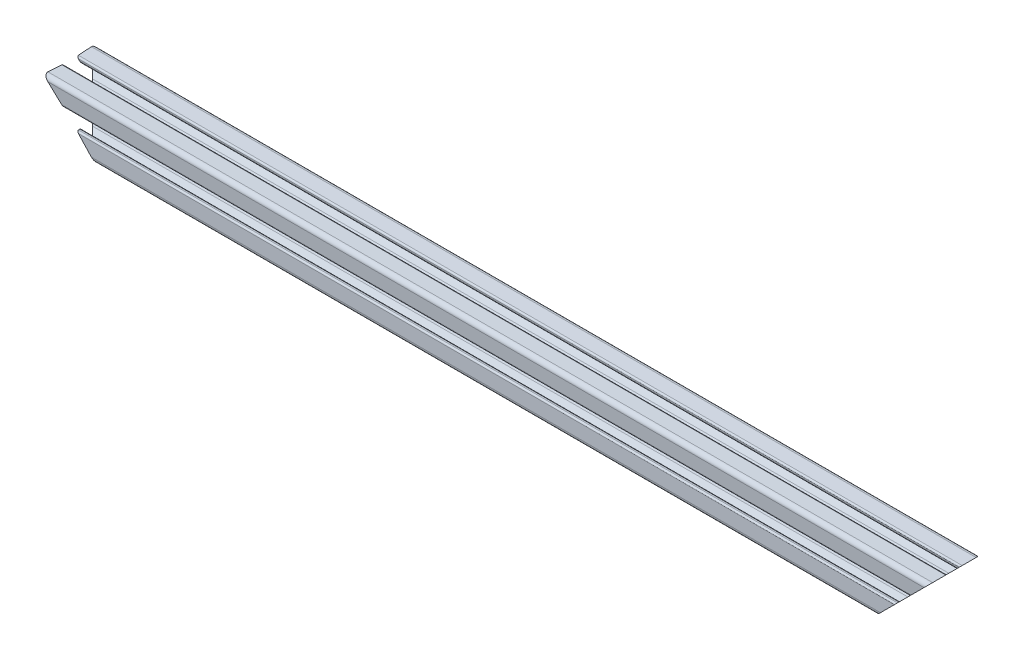
SolidWorks part; units mm, degrees
ref_plane "Front Plane" through (0, 0, 0) normal (0, 0, 1) x (1, 0, 0)
ref_plane "Top Plane" through (0, 0, 0) normal (0, 1, 0) x (1, 0, 0)
ref_plane "Right Plane" through (0, 0, 0) normal (1, 0, 0) x (0, 0, -1)
sketch "Sketch1" plane through (0, 0, 0) normal (1, 0, 0) x (0, 0, -1)
  line L0 (0, -12.7) -> (0, 12.7) construction
  line L1 (-7.874, 12.7) -> (7.874, 12.7) construction
  line L2 (-12.7, 0) -> (12.7, 0) construction
  line L3 (-7.874, 12.7) -> (-7.874, 4.826) construction
  line L4 (-3.302, 12.7) -> (3.302, 12.7) construction
  line L5 (-12.7, -12.7) -> (12.7, -12.7) construction
  line L6 (-12.7, 12.7) -> (12.7, 12.7) construction
  circle A0 centre (0, 0) radius 2.54 construction
  point P7 (0, 12.7)
  point P10 (0, 0)
  point P13 (0, 0)
  point P16 (0, 12.7)
  point P17 (-3.302, 12.7)
  point P18 (3.302, 12.7)
  point P21 (0, -12.7)
  point P24 (0, 12.7)
  dimension "Center Hole Diameter" = 5.08
  dimension "Rail Width" = 25.4
  dimension "Rail Height" = 25.4
  dimension "T-Slot Depth" = 7.874
  dimension "D1" = 15.748
  dimension "T-Slot Width" = 6.604
  dimension "D2" = 12.7
sketch "Sketch2" plane through (0, 0, 0) normal (0, 0, 1) x (1, 0, 0)
  line L0 (-215.5261, 0) -> (215.5261, 0) construction
  line L1 (0, 0) -> (0, 26.104) construction
  line L2 (215.5261, -12.7) -> (215.5261, 12.7) construction
  line L3 (-215.5261, -12.7) -> (-215.5261, 12.7) construction
  point P3 (-177.4261, 0)
  point P8 (0, 0)
  point P9 (177.4261, 0)
  point P12 (215.5261, 0)
  point P15 (-215.5261, 0)
  dimension "Length" = 431.0523
  dimension "D1" = 38.1
  dimension "D2" = 25.4
sketch "Sketch3" plane through (0, 0, 0) normal (1, 0, 0) x (0, 0, -1)
  line L0 (0, 4.826) -> (1.9842, 4.826)
  line L1 (0, -12.7) -> (0, 12.7) construction
  line L2 (4.2293, 5.7559) -> (7.5866, 9.1132)
  line L6 (7.0212, 10.4136) -> (4.0906, 10.3112)
  line L7 (3.302, 11.0728) -> (3.302, 11.7082)
  line L8 (-7.874, 12.7) -> (7.874, 12.7) construction
  line L10 (0, 0) -> (12.7, 12.7) construction
  line L13 (0, 4.826) -> (0, 2.54)
  line L14 (4.826, 0) -> (2.54, 0)
  line L31 (4.826, 0) -> (4.826, 1.9842)
  line L32 (4.0374, 12.4697) -> (10.5971, 12.6988)
  line L33 (-12.7, 0) -> (12.7, 0) construction
  line L34 (-12.7, 12.7) -> (12.7, 12.7) construction
  line L35 (5.7559, 4.2293) -> (9.1132, 7.5866)
  line L36 (0, 12.7) -> (12.7, 12.7) construction
  line L37 (12.7, 12.7) -> (12.7, 8.0234) construction
  line L38 (11.0728, 3.302) -> (11.7082, 3.302)
  line L39 (10.4136, 7.0212) -> (10.3112, 4.0906)
  line L40 (12.6988, 10.5971) -> (12.4697, 4.0374)
  arc A0 (2.54, 0) -> (0, 2.54) centre (0, 0) ccw
  arc A1 (1.9842, 4.826) -> (4.2293, 5.7559) centre (1.9842, 8.001) ccw
  circle A2 centre (0, 0) radius 2.54 construction
  arc A7 (3.302, 11.7082) -> (4.0374, 12.4697) centre (4.064, 11.7082) cw
  arc A8 (4.0906, 10.3112) -> (3.302, 11.0728) centre (4.064, 11.0728) cw
  arc A14 (4.826, 1.9842) -> (5.7559, 4.2293) centre (8.001, 1.9842) cw
  arc A16 (10.5971, 12.6988) -> (12.6988, 10.5971) centre (10.668, 10.668) cw
  arc A17 (7.0212, 10.4136) -> (7.5866, 9.1132) centre (7.0478, 9.652) cw
  arc A18 (10.4136, 7.0212) -> (9.1132, 7.5866) centre (9.652, 7.0478) ccw
  arc A19 (10.3112, 4.0906) -> (11.0728, 3.302) centre (11.0728, 4.064) ccw
  arc A20 (11.7082, 3.302) -> (12.4697, 4.0374) centre (11.7082, 4.064) ccw
  point P37 (3.2994, 4.826)
  point P49 (12.7, 3.302)
  point P52 (3.302, 12.7)
  point P55 (3.302, 10.2837)
  dimension "D4" = 3.175
  dimension "D9" = 2.159
  dimension "D12" = 0.762
  dimension "D3" = 2.032
  dimension "D8" = 0.762
  dimension "D2" = 45
  dimension "D5" = 2
  dimension "D6" = 45
  dimension "D7" = 2.159
extrude "Boss-Extrude1" add sketch "Sketch3" against normal up to vertex (215.5261 mm away) and the other way up to vertex (215.5261 mm away) up to point (-215.5261, 0, 0) other way up to point (215.5261, 0, 0)
mirror "Mirror1" about plane through (0, 0, 0) normal (0, 1, 0) of bodies 104
mirror "Mirror2" about plane through (0, 0, 0) normal (0, 0, 1) of bodies 105
sketch "Sketch4" plane through (-215.5261, 0, 0) normal (-1, 0, 0) x (0, 0, 1)
  arc A0 (12.6988, 10.5971) -> (10.5971, 12.6988) centre (10.668, 10.668) ccw construction
  arc A1 (10.5971, -12.6988) -> (12.6988, -10.5971) centre (10.668, -10.668) ccw construction
  point P0 (12.1048, 12.1048)
  point P1 (12.1048, -12.1048)
  point P5 (10.4144, -11.2551)
sketch "Sketch5" plane through (215.5261, 0, 0) normal (1, 0, 0) x (0, 0, -1)
  line L0 (10.5971, -12.6988) -> (12.6988, -12.6988)
  line L1 (12.6988, -12.6988) -> (12.6988, -10.5971)
  line L4 (10.668, 12.7) -> (12.7, 12.7)
  line L5 (12.7, 12.7) -> (12.6988, 10.5971)
  line L6 (12.6988, -12.6988) -> (12.7, 12.7)
  arc A0 (12.6988, 10.5971) -> (10.5971, 12.6988) centre (10.668, 10.668) ccw construction
  dimension "D1" = 90
sketch "Sketch6" plane through (-215.5261, 0, 0) normal (-1, 0, 0) x (0, 0, 1)
  line L0 (-12.6988, -10.5971) -> (-12.6988, -12.6988)
  line L1 (-12.6988, -12.6988) -> (-10.5971, -12.6988)
sketch "Sketch7" plane through (0, 0.43, -12.3137) normal (0, 0.0349, -0.9994) x (-1, 0, 0)
  line L0 (-215.5261, -13.1342) -> (-190.1261, -13.1342)
  line L1 (-215.5261, -13.1342) -> (-215.5261, -11.0338) construction
  line L2 (-215.5261, -13.0609) -> (-215.5261, -13.1342) construction
  dimension "D1" = 25.4
ref_plane "Plane7" through (0, 0, -12.6988) normal (0, 0, -1) x (-1, 0, 0)
sketch "Sketch13" plane through (0, 0, -12.6988) normal (0, 0, -1) x (-1, 0, 0)
  line L0 (-215.5261, 12.7) -> (-190.1261, -12.6962)
extrude "Cut-Extrude2" cut sketch "Sketch13" against normal through all and the other way through all flip side to cut
sketch "Sketch14" plane through (-215.5261, 0, 0) normal (-1, 0, 0) x (0, 0, 1)
  line L0 (-12.6988, 10.5971) -> (-12.7, 12.7)
  line L1 (-12.7, 12.7) -> (-10.668, 12.7)
sketch "Sketch15" plane through (0, 0, -12.6988) normal (0, 0, -1) x (-1, 0, 0)
  line L0 (215.5261, -12.6988) -> (-215.5261, -12.6988)
  line L1 (215.5261, -12.6988) -> (190.1261, -12.6988)
  dimension "D1" = 25.4
sketch "Sketch16" plane through (0, 0, -12.6988) normal (0, 0, -1) x (-1, 0, 0)
  line L0 (215.5261, -12.6988) -> (215.5261, 12.7021)
  line L1 (215.5261, 12.7021) -> (190.1261, -12.6988)
extrude "Cut-Extrude3" cut sketch "Sketch16" against normal through all and the other way through all
equation "\"D1@Sketch2\"=\"Rail Height@Sketch1\"*1.5"
equation "\"D2@Sketch2\"=\"Rail Height@Sketch1\""
